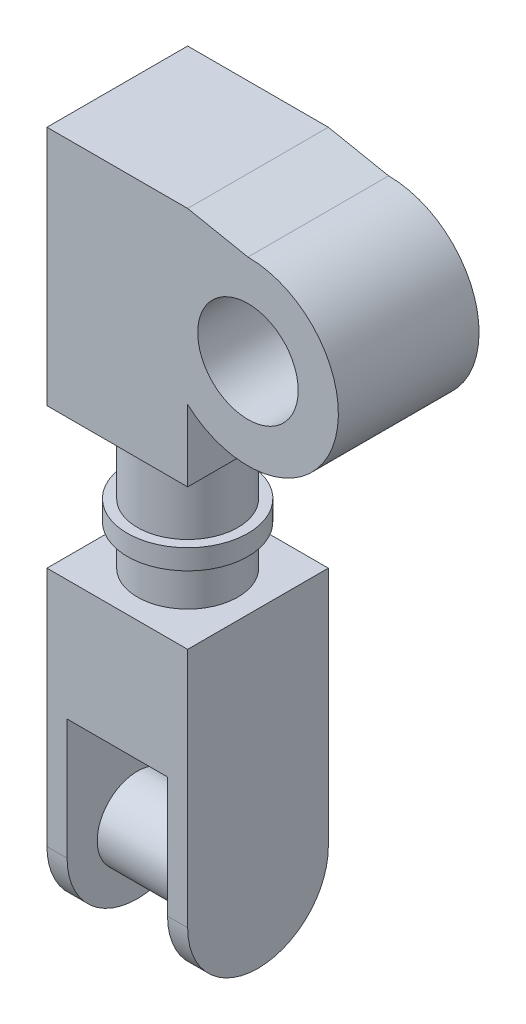
SolidWorks part; units mm, degrees
ref_plane "Front Plane" through (0, 0, 0) normal (0, 0, 1) x (1, 0, 0)
ref_plane "Top Plane" through (0, 0, 0) normal (0, 1, 0) x (1, 0, 0)
ref_plane "Right Plane" through (0, 0, 0) normal (1, 0, 0) x (0, 0, -1)
sketch "Sketch1" plane through (0, 0, 0) normal (0, 1, 0) x (1, 0, 0)
  line L1 (-35, -35) -> (35, -35)
  line L2 (-35, -35) -> (-35, 35)
  line L3 (-35, 35) -> (35, 35)
  line L4 (35, -35) -> (35, 35)
  line L5 (-35, -35) -> (35, 35) construction
  line L6 (-35, 35) -> (35, -35) construction
  point P0 (0, 0)
  dimension "D1" = 70
  dimension "D2" = 70
extrude "Boss-Extrude1" add sketch "Sketch1" along normal blind 120
sketch "Sketch2" plane through (0, 0, 0) normal (0, -1, 0) x (1, 0, 0)
  circle A0 centre (0, 0) radius 25
  dimension "D1" = 50
extrude "Boss-Extrude2" add sketch "Sketch2" along normal blind 40
sketch "Sketch3" plane through (0, -40, 0) normal (0, -1, 0) x (1, 0, 0)
  circle A0 centre (0, 0) radius 30
  dimension "D1" = 60
extrude "Boss-Extrude3" add sketch "Sketch3" along normal blind 10
sketch "Sketch4" plane through (0, 0, 35) normal (0, 0, 1) x (1, 0, 0)
  line L0 (35, 120) -> (65, 114.0482)
  line L1 (-35, 120) -> (35, 120) construction
  line L2 (35, 120) -> (35, 0) construction
  line L3 (35, 120) -> (35, 0)
  circle A0 centre (65, 69.0482) radius 25
  arc A1 (35, 35.5072) -> (65, 114.0482) centre (65, 69.0482) ccw
  dimension "D1" = 50
  dimension "D2" = 90
  dimension "D3" = 30
extrude "Boss-Extrude4" add sketch "Sketch4" against normal blind 70 contours L3 A1 L0 A0
sketch "Sketch5" plane through (0, -50, 0) normal (0, -1, 0) x (1, 0, 0)
  circle A0 centre (0, 0) radius 25
  dimension "D1" = 50
extrude "Boss-Extrude5" add sketch "Sketch5" along normal blind 20
sketch "Sketch6" plane through (0, 0, 0) normal (1, 0, 0) x (0, 0, -1)
  line L0 (0, 0) -> (0, -190) construction
  line L1 (-35, 0) -> (35, 0) construction
  line L2 (-25, -70) -> (25, -70) construction
  line L3 (35, -190) -> (35, -155)
  line L5 (-35, -155) -> (-35, -190)
  line L6 (-35, -190) -> (-35, -70)
  line L7 (-35, -70) -> (35, -70)
  line L8 (35, -70) -> (35, -155)
  arc A0 (-35, -190) -> (35, -190) centre (0, -190) ccw
  dimension "D1" = 70
  dimension "D2" = 120
extrude "Boss-Extrude6" add sketch "Sketch6" along normal mid plane 70
sketch "Sketch8" plane through (0, 0, 0) normal (1, 0, 0) x (0, 0, -1)
  line L0 (-35, -130) -> (35, -130)
  line L1 (-35, -70) -> (-35, -190) construction
  line L2 (35, -190) -> (35, -70) construction
  line L3 (35, -130) -> (35, -190)
  line L7 (-35, -70) -> (-35, -190)
  line L8 (35, -190) -> (35, -70)
  line L9 (35, -70) -> (-35, -70)
  line L10 (-35, -130) -> (-35, -190)
  line L11 (35, -190) -> (35, -130)
  arc A1 (-35, -190) -> (35, -190) centre (0, -190) ccw
  arc A2 (-35, -190) -> (35, -190) centre (0, -190) ccw
  dimension "D1" = 0
extrude "Cut-Extrude1" cut sketch "Sketch8" against normal mid plane 50 contours L10 A2 L3 L0
sketch3d "3DSketch1"
  line L3 (35, -70, 35) -> (35, -190, 35)
  line L4 (35, -190, -35) -> (35, -70, -35)
  line L5 (35, -70, -35) -> (35, -70, 35)
  line L6 (35, -70, 35) -> (35, -190, 35)
  line L7 (35, -190, -35) -> (35, -70, -35)
  line L8 (35, -70, -35) -> (35, -70, 35)
  arc A1 (35, -190, 35) -> (35, -190, -35) centre (35, -190, 0) ccw
  arc A2 (35, -190, 35) -> (35, -190, -35) centre (35, -190, 0) ccw
  point P6 (70, -190, 0)
  point P8 (70, -190, 0)
  dimension "D1" = 0
sketch "Sketch9" plane through (-25, 0, 0) normal (1, 0, 0) x (0, 0, -1)
  circle A0 centre (0, -190) radius 20
  dimension "D1" = 40
extrude "Boss-Extrude7" add sketch "Sketch9" along normal blind 50
